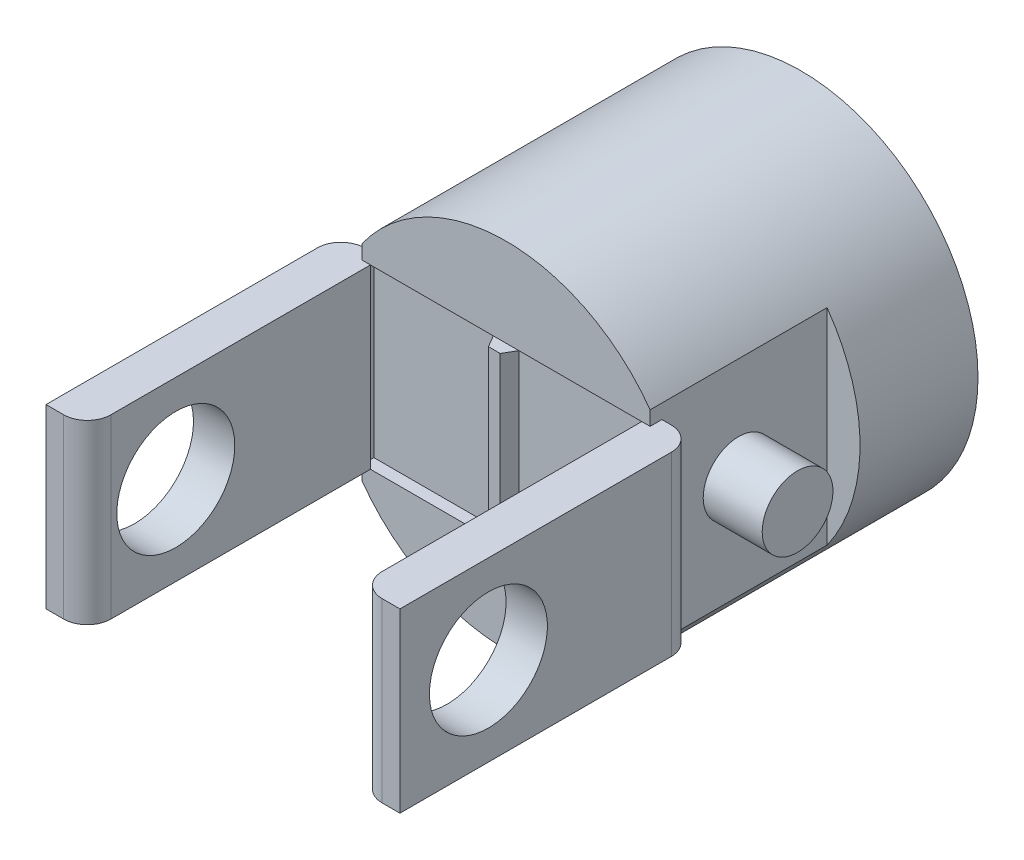
SolidWorks part; units mm, degrees
ref_plane "Front Plane" through (0, 0, 0) normal (0, 0, 1) x (1, 0, 0)
ref_plane "Top Plane" through (0, 0, 0) normal (0, 1, 0) x (1, 0, 0)
ref_plane "Right Plane" through (0, 0, 0) normal (1, 0, 0) x (0, 0, -1)
sketch "Sketch1" plane through (0, 0, 0) normal (0, 0, 1) x (1, 0, 0)
  circle A0 centre (0, 0) radius 30
  dimension "D1" = 60
extrude "Boss-Extrude1" add sketch "Sketch1" along normal blind 50
sketch "Sketch2" plane through (0, 0, 0) normal (0, 0, -1) x (-1, 0, 0)
  circle A0 centre (0, 0) radius 23
  dimension "D1" = 46
extrude "Cut-Extrude1" cut sketch "Sketch2" against normal blind 20
sketch "Sketch3" plane through (0, 0, 50) normal (0, 0, 1) x (1, 0, 0)
  line L0 (0, 12.7898) -> (0, 0) construction
  line L1 (-24.4132, 17.4355) -> (-24.4132, -17.4355)
  line L6 (24.4132, 17.4355) -> (24.4132, -17.4355)
  circle A0 centre (0, 0) radius 30 construction
  arc A1 (-24.4132, 17.4355) -> (-24.4132, -17.4355) centre (0, 0) ccw
  arc A2 (24.4132, 17.4355) -> (24.4132, -17.4355) centre (0, 0) cw
  point P4 (24.4132, 0)
  dimension "D1" = 30
  dimension "D2" = 34.8709
extrude "Cut-Extrude2" cut sketch "Sketch3" against normal blind 30
sketch "Sketch5" plane through (24.4132, 0, 0) normal (1, 0, 0) x (0, 0, -1)
  line L0 (-20, 17.4355) -> (-50, -17.4355) construction
  circle A0 centre (-35, 0) radius 6
  dimension "D1" = 12
extrude "Boss-Extrude3" add sketch "Sketch5" along normal blind 10
sketch "Sketch6" plane through (0, 0, 50) normal (0, 0, 1) x (1, 0, 0)
  line L1 (-24.4132, 15) -> (24.4132, 15)
  line L2 (-24.4132, 15) -> (-24.4132, -15)
  line L3 (-24.4132, -15) -> (24.4132, -15)
  line L4 (24.4132, 15) -> (24.4132, -15)
  line L5 (24.4132, 17.4355) -> (24.4132, -17.4355) construction
  line L6 (-24.4132, 15) -> (24.4132, -15) construction
  line L7 (-24.4132, -17.4355) -> (-24.4132, 17.4355) construction
  circle A0 centre (0, 0) radius 30 construction
  circle A1 centre (0, 0) radius 30 construction
  dimension "D1" = 15
  dimension "D2" = 15
extrude "Cut-Extrude3" cut sketch "Sketch6" against normal blind 2
sketch "Sketch7" plane through (0, 15, 0) normal (0, -1, 0) x (1, 0, 0)
  line L0 (-23, 98) -> (-23, 14)
  line L1 (-30, 48) -> (30, 48)
  line L2 (-30, 48) -> (-30, 98)
  line L3 (-30, 98) -> (-23, 98)
  line L4 (30, 48) -> (30, 98)
  line L5 (23, 14) -> (23, 98)
  line L6 (23, 14) -> (1, 52)
  line L7 (1, 52) -> (-1, 52)
  line L8 (-1, 52) -> (-23, 14)
  line L9 (23, 98) -> (30, 98)
  point P12 (0, 52)
  line M1 (24.4132, 50) -> (-24.4132, 50)
  line M3 (-24.4132, 48) -> (24.4132, 48)
  line M4 (24.4132, 48) -> (24.4132, 50)
  line M17 (-24.4132, 50) -> (-24.4132, 48)
  dimension "D2" = 60
  dimension "D3" = 5.5868
  dimension "D4" = 50
  dimension "D5" = 7
  dimension "D6" = 7
  dimension "D7" = 38
  dimension "D8" = 23
  dimension "D9" = 2
  dimension "D10" = 4
extrude "Boss-Extrude4" add sketch "Sketch7" along normal blind 30 contours L3 L2 L1 L0 M17 M1 | L8 L0 M3 | L7 L8 L6 M1 | L6 L5 L1 | L9 L5 L1 L4 M1 M4
sketch "Sketch8" plane through (-30, 0, 0) normal (-1, 0, 0) x (0, 0, 1)
  line L1 (98, -15) -> (98, 15) construction
  circle A0 centre (83, 0) radius 10
  dimension "D1" = 20
  dimension "D3" = 15
extrude "Cut-Extrude4" cut sketch "Sketch8" against normal through all
fillet "Fillet1" radius 4 2 edges at (30, 0, 48) (23, 0, 98)
fillet "Fillet2" radius 4 2 edges at (-23, 0, 98) (-30, 0, 48)
sketch "Sketch9" plane through (0, 0, 20) normal (0, 0, -1) x (-1, 0, 0)
  line L0 (0, 0) -> (0, -5) construction
  line L4 (0, -11.9499) -> (-1, -11.9499)
  line L5 (-1, -9.9499) -> (-1, -11.9499)
  line L8 (0, -11.9499) -> (1, -11.9499)
  line L9 (1, -9.9499) -> (1, -11.9499)
  arc A0 (1, -9.9499) -> (-1, -9.9499) centre (0, 0) ccw
  dimension "D1" = 20
  dimension "D2" = 2
  dimension "D3" = 1
  dimension "D4" = 1
extrude "Boss-Extrude5" add sketch "Sketch9" along normal blind 10
sketch "Sketch10" plane through (0, 0, 0) normal (0, 1, 0) x (1, 0, 0)
  point P0 (0, -41.5)
  dimension "D1" = 41.5
